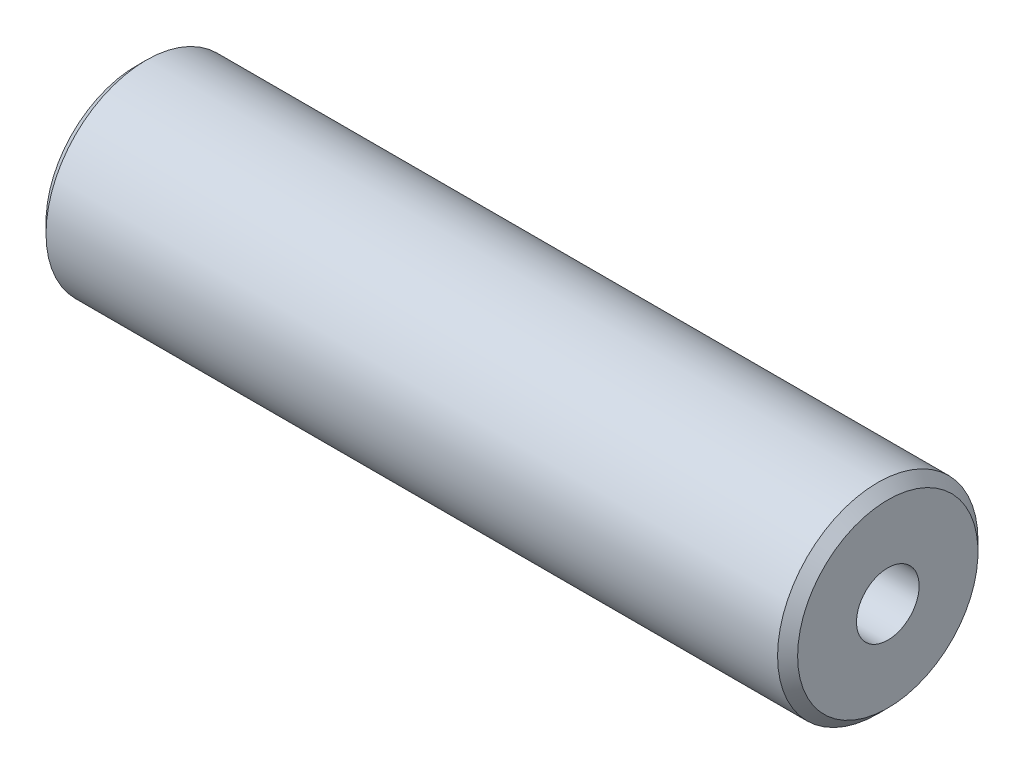
SolidWorks part; units mm, degrees
material "A2017-T4"
ref_plane "Front Plane" through (0, 0, 0) normal (0, 0, 1) x (1, 0, 0)
ref_plane "Top Plane" through (0, 0, 0) normal (0, 1, 0) x (1, 0, 0)
ref_plane "Right Plane" through (0, 0, 0) normal (1, 0, 0) x (0, 0, -1)
sketch "Sketch1" plane through (0, 0, 0) normal (0, 0, 1) x (1, 0, 0)
  line L0 (0, 4) -> (30, 4)
  line L1 (0, 0) -> (30, 0)
  line L2 (0, 4) -> (0, 0)
  line L3 (0, 0) -> (30, 0) construction
  line L4 (30, 4) -> (30, 0)
  dimension "L" = 30
  dimension "D" = 8
revolve "Revolve1" add sketch "Sketch1" angle 360 about L1
chamfer "Chamfer1" distance 0.4 angle 45 2 edges at (30, 0, 4) (0, 0, 4)
ref_plane "Dim. SC" through (6, 0, 0) normal (1, 0, 0) x (0, 0, -1)
hole_wizard "Tapped Hole1" [suppressed] positions "Sketch3" profile "Sketch2" tap size "M4x0.7" standard "JIS"
sketch "Sketch3" [suppressed] plane through (0, 0, 0) normal (-1, 0, 0) x (0, 0, 1)
  point P0 (0, 0)
sketch "Sketch2" [suppressed] plane through (0, 0, 0) normal (0, 1, 0) x (0, 0, 1)
  line L0 (0, 0) -> (0, 12.4914)
  line L1 (0, 12.4914) -> (1.65, 11.5)
  line L2 (1.65, 11.5) -> (1.65, 0)
  line L3 (2, 0) -> (2, 11.5) construction
  line L5 (1.65, 0) -> (0, 0)
  line L10 (0, 12.4914) -> (-1.65, 11.5) construction
  line L11 (0, 0) -> (0, 12.4914) construction
  dimension "Tap Drill Dia." = 3.3
  dimension "Tap Drill Depth" = 11.5
  dimension "Drill Angle" = 118
  dimension "M" = 3
cosmetic thread "Hole Thread1" [suppressed] parameters "Mx2"=8, "M"=3
hole_wizard "Tapped Hole2" [suppressed] positions "Sketch5" profile "Sketch4" tap size "M4x0.7" standard "JIS"
sketch "Sketch5" [suppressed] plane through (30, 0, 0) normal (1, 0, 0) x (0, 0, -1)
  point P0 (0, 0)
sketch "Sketch4" [suppressed] plane through (30, 0, 0) normal (0, 1, 0) x (0, 0, -1)
  line L0 (0, 0) -> (0, 12.4914)
  line L1 (0, 12.4914) -> (1.65, 11.5)
  line L2 (1.65, 11.5) -> (1.65, 0)
  line L5 (1.65, 0) -> (0, 0)
  line L10 (0, 12.4914) -> (-1.65, 11.5) construction
  line L11 (0, 0) -> (0, 12.4914) construction
  dimension "Tap Drill Dia." = 3.3
  dimension "Tap Drill Depth" = 11.5
  dimension "Drill Angle" = 118
cosmetic thread "Hole Thread2" [suppressed] parameters "Mx2"=8, "M"=3
hole_wizard "Tapped Hole3" [suppressed] positions "Sketch7" profile "Sketch6" tap size "M4x0.7" standard "JIS"
sketch "Sketch7" [suppressed] plane through (0, 0, 0) normal (-1, 0, 0) x (0, 0, 1)
  point P0 (0, 0)
sketch "Sketch6" [suppressed] plane through (0, 0, 0) normal (0, 1, 0) x (0, 0, 1)
  line L0 (0, 0) -> (0, 30)
  line L1 (0, 30) -> (1.65, 30)
  line L2 (1.65, 30) -> (1.65, 0)
  line L5 (1.65, 0) -> (0, 0)
  line L11 (0, 0) -> (0, 30) construction
  dimension "Thru Tap Drill Dia." = 3.3
  dimension "Thru Tap Drill Depth" = 30
cosmetic thread "Hole Thread3" [suppressed] parameters "M"=3
sketch "Sketch8" [suppressed] plane through (0, 0, 0) normal (0, 1, 0) x (1, 0, 0)
  line L0 (10, -3.5) -> (10, -4) construction
  line L1 (6, 4) -> (14, 4)
  line L2 (6, 4) -> (6, 3.5)
  line L3 (6, 3.5) -> (14, 3.5)
  line L4 (14, 4) -> (14, 3.5)
  line L5 (6, -3.5) -> (14, -3.5)
  line L6 (6, -3.5) -> (6, -4)
  line L7 (6, -4) -> (14, -4)
  line L8 (14, -3.5) -> (14, -4)
  line L12 (0, 0) -> (30, 0) construction
  dimension "S" = 6
  dimension "W" = 7
  dimension "L1_s" = 8
  dimension "D" = 8
  dimension "L1_s_L" = 8
extrude "Cut-Extrude1" [suppressed] cut sketch "Sketch8" against normal through all and the other way through all
ref_plane "L Dimension Selectable_SEC" [suppressed] through (10, 0, 0) normal (1, 0, 0) x (0, 0, -1)
hole_wizard "Tapped Hole4" [suppressed] positions "Sketch10" profile "Sketch9" tap size "M4x0.7" standard "JIS"
sketch "Sketch10" [suppressed] plane through (0, 0, 0) normal (-1, 0, 0) x (0, 0, 1)
  point P0 (0, 0)
sketch "Sketch9" [suppressed] plane through (0, 0, 0) normal (0, 1, 0) x (0, 0, 1)
  line L0 (0, 0) -> (0, 12.4914)
  line L1 (0, 12.4914) -> (1.65, 11.5)
  line L2 (1.65, 11.5) -> (1.65, 0)
  line L3 (2, 0) -> (2, 11.5) construction
  line L5 (1.65, 0) -> (0, 0)
  line L10 (0, 12.4914) -> (-1.65, 11.5) construction
  line L11 (0, 0) -> (0, 12.4914) construction
  dimension "Tap Drill Dia." = 3.3
  dimension "Tap Drill Depth" = 11.5
  dimension "Drill Angle" = 118
  dimension "M" = 3
cosmetic thread "Hole Thread4" [suppressed] parameters "Mx2"=8, "M"=3
hole_wizard "Tapped Hole5" [suppressed] positions "Sketch12" profile "Sketch11" tap size "M4x0.7" standard "JIS"
sketch "Sketch12" [suppressed] plane through (30, 0, 0) normal (1, 0, 0) x (0, 0, -1)
  point P0 (0, 0)
sketch "Sketch11" [suppressed] plane through (30, 0, 0) normal (0, 1, 0) x (0, 0, -1)
  line L0 (0, 0) -> (0, 12.4914)
  line L1 (0, 12.4914) -> (1.65, 11.5)
  line L2 (1.65, 11.5) -> (1.65, 0)
  line L5 (1.65, 0) -> (0, 0)
  line L10 (0, 12.4914) -> (-1.65, 11.5) construction
  line L11 (0, 0) -> (0, 12.4914) construction
  dimension "Tap Drill Dia." = 3.3
  dimension "Tap Drill Depth" = 11.5
  dimension "Drill Angle" = 118
cosmetic thread "Hole Thread5" [suppressed] parameters "Mx2"=8, "M"=3
hole_wizard "Tapped Hole6" [suppressed] positions "Sketch14" profile "Sketch13" tap size "M4x0.7" standard "JIS"
sketch "Sketch14" [suppressed] plane through (0, 0, 0) normal (-1, 0, 0) x (0, 0, 1)
  point P0 (0, 0)
sketch "Sketch13" [suppressed] plane through (0, 0, 0) normal (0, 1, 0) x (0, 0, 1)
  line L0 (0, 0) -> (0, 30)
  line L1 (0, 30) -> (1.65, 30)
  line L2 (1.65, 30) -> (1.65, 0)
  line L5 (1.65, 0) -> (0, 0)
  line L11 (0, 0) -> (0, 30) construction
  dimension "Thru Tap Drill Dia." = 3.3
  dimension "Thru Tap Drill Depth" = 30
cosmetic thread "Hole Thread6" [suppressed] parameters "M"=3
hole_wizard "Tapped Hole7" [suppressed] positions "Sketch16" profile "Sketch15" tap size "M4x0.7" standard "JIS"
sketch "Sketch16" [suppressed] plane through (0, 0, 0) normal (-1, 0, 0) x (0, 0, 1)
  point P0 (0, 0)
sketch "Sketch15" [suppressed] plane through (0, 0, 0) normal (0, 1, 0) x (0, 0, 1)
  line L0 (0, 0) -> (0, 12.4914)
  line L1 (0, 12.4914) -> (1.65, 11.5)
  line L2 (1.65, 11.5) -> (1.65, 0)
  line L3 (2, 0) -> (2, 11.5) construction
  line L5 (1.65, 0) -> (0, 0)
  line L10 (0, 12.4914) -> (-1.65, 11.5) construction
  line L11 (0, 0) -> (0, 12.4914) construction
  dimension "Tap Drill Dia." = 3.3
  dimension "Tap Drill Depth" = 11.5
  dimension "Drill Angle" = 118
  dimension "M" = 3
cosmetic thread "Hole Thread7" [suppressed] parameters "Mx2"=8, "M"=3
hole_wizard "Tapped Hole8" [suppressed] positions "Sketch18" profile "Sketch17" tap size "M4x0.7" standard "JIS"
sketch "Sketch18" [suppressed] plane through (30, 0, 0) normal (1, 0, 0) x (0, 0, -1)
  point P0 (0, 0)
sketch "Sketch17" [suppressed] plane through (30, 0, 0) normal (0, 1, 0) x (0, 0, -1)
  line L0 (0, 0) -> (0, 12.4914)
  line L1 (0, 12.4914) -> (1.65, 11.5)
  line L2 (1.65, 11.5) -> (1.65, 0)
  line L5 (1.65, 0) -> (0, 0)
  line L10 (0, 12.4914) -> (-1.65, 11.5) construction
  line L11 (0, 0) -> (0, 12.4914) construction
  dimension "Tap Drill Dia." = 3.3
  dimension "Tap Drill Depth" = 11.5
  dimension "Drill Angle" = 118
cosmetic thread "Hole Thread8" [suppressed] parameters "Mx2"=8, "M"=3
hole_wizard "Tapped Hole9" [suppressed] positions "Sketch20" profile "Sketch19" tap size "M4x0.7" standard "JIS"
sketch "Sketch20" [suppressed] plane through (0, 0, 0) normal (-1, 0, 0) x (0, 0, 1)
  point P0 (0, 0)
sketch "Sketch19" [suppressed] plane through (0, 0, 0) normal (0, 1, 0) x (0, 0, 1)
  line L0 (0, 0) -> (0, 30)
  line L1 (0, 30) -> (1.65, 30)
  line L2 (1.65, 30) -> (1.65, 0)
  line L5 (1.65, 0) -> (0, 0)
  line L11 (0, 0) -> (0, 30) construction
  dimension "Thru Tap Drill Dia." = 3.3
  dimension "Thru Tap Drill Depth" = 30
cosmetic thread "Hole Thread9" [suppressed] parameters "M"=3
sketch "Sketch21" [suppressed] plane through (0, 0, 0) normal (0, 1, 0) x (1, 0, 0)
  line L0 (0, 0) -> (30, 0) construction
  line L1 (6, 4) -> (14, 4)
  line L2 (6, 4) -> (6, 3.5)
  line L3 (6, 3.5) -> (14, 3.5)
  line L4 (14, 4) -> (14, 3.5)
  line L5 (6, -3.5) -> (14, -3.5)
  line L6 (6, -3.5) -> (6, -4)
  line L7 (6, -4) -> (14, -4)
  line L8 (14, -3.5) -> (14, -4)
  line L9 (10, -3.5) -> (10, -4) construction
  line L18 (6, -4.4) -> (6, 4.4) construction
  line L19 (30, -3.6) -> (30, 3.6) construction
  dimension "W" = 7
  dimension "L1_s" = 8
  dimension "D" = 8
  dimension "L1_s_L" = 8
extrude "Cut-Extrude2" [suppressed] cut sketch "Sketch21" against normal through all and the other way through all
ref_plane "L Dimension Cofigurable, Wrench Flats_SEC" [suppressed] through (10, 0, 0) normal (1, 0, 0) x (0, 0, -1)
hole_wizard "Tapped Hole10" positions "Sketch23" profile "Sketch22" tap size "M4x0.7" standard "JIS"
sketch "Sketch23" plane through (0, 0, 0) normal (-1, 0, 0) x (0, 0, 1)
  point P0 (0, 0)
sketch "Sketch22" plane through (0, 0, 0) normal (0, 1, 0) x (0, 0, 1)
  line L0 (0, 0) -> (0, 9.2511)
  line L1 (0, 9.2511) -> (1.25, 8.5)
  line L2 (1.25, 8.5) -> (1.25, 0)
  line L3 (1.5, 0) -> (1.5, 8.5) construction
  line L5 (1.25, 0) -> (0, 0)
  line L10 (0, 9.2511) -> (-1.25, 8.5) construction
  line L11 (0, 0) -> (0, 9.2511) construction
  dimension "Tap Drill Dia." = 2.5
  dimension "Tap Drill Depth" = 8.5
  dimension "Drill Angle" = 118
  dimension "M" = 3
  dimension "Pilot hole Tip" = 9.2511
cosmetic thread "Hole Thread10" parameters "Mx2"=6, "M"=3
hole_wizard "Tapped Hole11" positions "Sketch25" profile "Sketch24" tap size "M4x0.7" standard "JIS"
sketch "Sketch25" plane through (30, 0, 0) normal (1, 0, 0) x (0, 0, -1)
  point P0 (0, 0)
sketch "Sketch24" plane through (30, 0, 0) normal (0, 1, 0) x (0, 0, -1)
  line L0 (0, 9.2511) -> (0, 0)
  line L1 (0, 9.2511) -> (1.25, 8.5)
  line L2 (1.25, 8.5) -> (1.25, 0)
  line L3 (1.5, 8.5) -> (1.5, 0) construction
  line L5 (1.25, 0) -> (0, 0)
  line L10 (0, 9.2511) -> (-1.25, 8.5) construction
  line L11 (0, 0) -> (0, 9.2511) construction
  dimension "Tap Drill Dia." = 2.5
  dimension "Tap Drill Depth" = 8.5
  dimension "Drill Angle" = 118
  dimension "N" = 3
  dimension "Pilot hole Tip" = 9.2511
cosmetic thread "Hole Thread11" parameters "Nx2"=6, "N"=3
sketch "Sketch26" plane through (0, 0, 0) normal (-1, 0, 0) x (0, 0, 1)
  circle A0 centre (0, 0) radius 1.25
  circle A1 centre (0, 0) radius 1.25
  dimension "MSM_1" = 2.5
  dimension "MSM_2" = 2.5
extrude "Boss-Extrude1" [suppressed] add sketch "Sketch26" against normal blind 6
sketch "Sketch27" plane through (30, 0, 0) normal (1, 0, 0) x (0, 0, -1)
  circle A0 centre (0, 0) radius 1.25
  circle A1 centre (0, 0) radius 1.25
  dimension "MSM_2" = 2.5
  dimension "MSM_1" = 2.5
extrude "Boss-Extrude2" [suppressed] add sketch "Sketch27" against normal blind 6
hole_wizard "Tapped Hole12" [suppressed] positions "Sketch29" profile "Sketch28" tap size "M4x0.7" standard "JIS"
sketch "Sketch29" [suppressed] plane through (0, 0, 0) normal (-1, 0, 0) x (0, 0, 1)
  point P0 (0, 0)
sketch "Sketch28" [suppressed] plane through (0, 0, 0) normal (0, 1, 0) x (0, 0, 1)
  line L0 (0, 0) -> (0, 12.4914)
  line L1 (0, 12.4914) -> (1.65, 11.5)
  line L2 (1.65, 11.5) -> (1.65, 0)
  line L3 (2, 0) -> (2, 11.5) construction
  line L5 (1.65, 0) -> (0, 0)
  line L10 (0, 12.4914) -> (-1.65, 11.5) construction
  line L11 (0, 0) -> (0, 12.4914) construction
  dimension "Tap Drill Dia." = 3.3
  dimension "Tap Drill Depth" = 11.5
  dimension "Drill Angle" = 118
  dimension "M" = 3
  dimension "Pilot hole Tip" = 12.4914
cosmetic thread "Hole Thread12" [suppressed] parameters "Mx2"=8, "M"=3
hole_wizard "Tapped Hole13" [suppressed] positions "Sketch31" profile "Sketch30" tap size "M4x0.7" standard "JIS"
sketch "Sketch31" [suppressed] plane through (30, 0, 0) normal (1, 0, 0) x (0, 0, -1)
  point P0 (0, 0)
sketch "Sketch30" [suppressed] plane through (30, 0, 0) normal (0, 1, 0) x (0, 0, -1)
  line L0 (0, 12.4914) -> (0, 0)
  line L1 (0, 12.4914) -> (1.65, 11.5)
  line L2 (1.65, 11.5) -> (1.65, 0)
  line L3 (2, 11.5) -> (2, 0) construction
  line L5 (1.65, 0) -> (0, 0)
  line L10 (0, 12.4914) -> (-1.65, 11.5) construction
  line L11 (0, 0) -> (0, 12.4914) construction
  dimension "Tap Drill Dia." = 3.3
  dimension "Tap Drill Depth" = 11.5
  dimension "Drill Angle" = 118
  dimension "N" = 3
  dimension "Pilot hole Tip" = 12.4914
cosmetic thread "Hole Thread13" [suppressed] parameters "Nx2"=8, "N"=3
sketch "Sketch32" [suppressed] plane through (0, 0, 0) normal (-1, 0, 0) x (0, 0, 1)
  circle A0 centre (0, 0) radius 1.65
  circle A1 centre (0, 0) radius 1.65
  dimension "MSM_2" = 2.5
  dimension "MSM_1" = 2.5
extrude "Boss-Extrude3" [suppressed] add sketch "Sketch32" against normal blind 6
sketch "Sketch33" [suppressed] plane through (30, 0, 0) normal (1, 0, 0) x (0, 0, -1)
  circle A0 centre (0, 0) radius 1.65
  circle A1 centre (0, 0) radius 1.65
  dimension "MSM_1" = 2.5
  dimension "MSM_2" = 2.5
extrude "Boss-Extrude4" [suppressed] add sketch "Sketch33" against normal blind 6
sketch "Sketch34" [suppressed] plane through (0, 0, 0) normal (0, 1, 0) x (1, 0, 0)
  line L0 (10, -3.5) -> (10, -4) construction
  line L1 (6, 4) -> (14, 4)
  line L2 (6, 4) -> (6, 3.5)
  line L3 (6, 3.5) -> (14, 3.5)
  line L4 (14, 4) -> (14, 3.5)
  line L5 (6, -3.5) -> (14, -3.5)
  line L6 (6, -3.5) -> (6, -4)
  line L7 (6, -4) -> (14, -4)
  line L8 (14, -3.5) -> (14, -4)
  line L9 (30, -3.6) -> (30, 3.6) construction
  line L12 (0, 0) -> (30, 0) construction
  line L15 (6, -4.4) -> (6, 4.4) construction
  dimension "L1_s" = 8
  dimension "W" = 7
  dimension "D" = 8
  dimension "L1_s_L" = 8
extrude "Cut-Extrude3" [suppressed] cut sketch "Sketch34" against normal through all and the other way through all
ref_plane "L Dimension Configurable, Thread Dia. Configurable, Wrench Flats_SEC" [suppressed] through (10, 0, 0) normal (1, 0, 0) x (0, 0, -1)
hole_wizard "Tapped Hole14" [suppressed] positions "Sketch36" profile "Sketch35" tap size "M4x0.7" standard "JIS"
sketch "Sketch36" [suppressed] plane through (0, 0, 0) normal (-1, 0, 0) x (0, 0, 1)
  point P0 (0, 0)
sketch "Sketch35" [suppressed] plane through (0, 0, 0) normal (0, 1, 0) x (0, 0, 1)
  line L0 (0, 0) -> (0, 16.4914)
  line L1 (0, 16.4914) -> (1.65, 15.5)
  line L2 (1.65, 15.5) -> (1.65, 0)
  line L5 (1.65, 0) -> (0, 0)
  line L10 (0, 16.4914) -> (-1.65, 15.5) construction
  line L11 (0, 0) -> (0, 16.4914) construction
  dimension "Tap Drill Dia." = 3.3
  dimension "Tap Drill Depth" = 15.5
  dimension "Drill Angle" = 118
cosmetic thread "Hole Thread14" [suppressed] parameters "Mx3"=12, "MD"=4
hole_wizard "Tapped Hole15" [suppressed] positions "Sketch38" profile "Sketch37" tap size "M4x0.7" standard "JIS"
sketch "Sketch38" [suppressed] plane through (30, -2.1135, -9.2544) normal (1, 0, 0) x (0, 0, -1)
  point P0 (-9.2544, 2.1135)
sketch "Sketch37" [suppressed] plane through (30, 0, 0) normal (0, 1, 0) x (0, 0, -1)
  line L0 (0, 0) -> (0, 16.4914)
  line L1 (0, 16.4914) -> (1.65, 15.5)
  line L2 (1.65, 15.5) -> (1.65, 0)
  line L5 (1.65, 0) -> (0, 0)
  line L10 (0, 16.4914) -> (-1.65, 15.5) construction
  line L11 (0, 0) -> (0, 16.4914) construction
  dimension "Tap Drill Dia." = 3.3
  dimension "Tap Drill Depth" = 15.5
  dimension "Drill Angle" = 118
cosmetic thread "Hole Thread15" [suppressed] parameters "Nx3"=12, "ND"=4
ref_plane "Plane1" [suppressed] through (0, 4, 0) normal (0, 1, 0) x (1, 0, 0)
hole_wizard "Diameter Hole1" [suppressed] positions "Sketch40" profile "Sketch39" hole size "Ø2.5" standard "JIS"
sketch "Sketch40" [suppressed] plane through (0, 4, 0) normal (0, 1, 0) x (1, 0, 0)
  line L0 (0, 3.8) -> (0, -3.8) construction
  point P0 (7, 0)
  dimension "HL" = 7
sketch "Sketch39" [suppressed] plane through (7, 4, 0) normal (1, 0, 0) x (0, 0, 1)
  line L0 (0, 0) -> (0, 8)
  line L1 (0, 8) -> (1.25, 8)
  line L2 (1.25, 8) -> (1.25, 0)
  line L5 (1.25, 0) -> (0, 0)
  line L11 (0, 0) -> (0, 8) construction
  dimension "D_s" = 2.5
  dimension "Thru Hole Depth" = 8
equation "\"Plane dim\"= \"D@Sketch1\" * 0.5"
equation "\"D1@Boss-Extrude1\" = \"M\" * 2"
equation "\"D1@Boss-Extrude2\" = \"N\" * 2"
equation "\"D1@Boss-Extrude3\" = \"M\" * 2"
equation "\"D1@Boss-Extrude4\" = \"N\" * 2"
equation "\"M\"=3"
equation "\"N\"=3"
